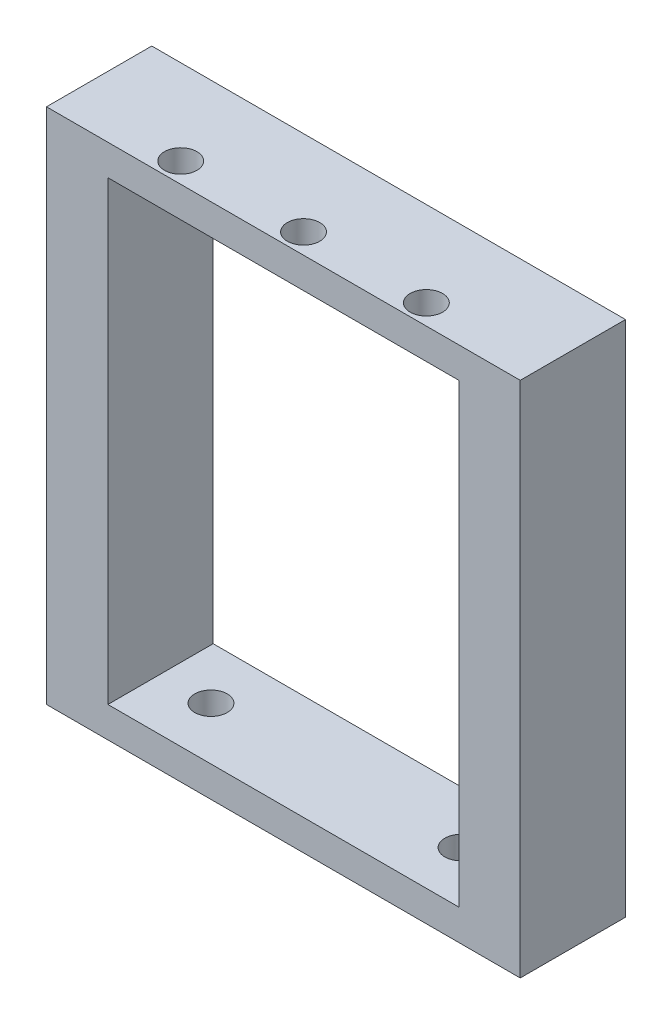
SolidWorks part; units mm, degrees
ref_plane "Front Plane" through (0, 0, 0) normal (0, 0, 1) x (1, 0, 0)
ref_plane "Top Plane" through (0, 0, 0) normal (0, 1, 0) x (1, 0, 0)
ref_plane "Right Plane" through (0, 0, 0) normal (1, 0, 0) x (0, 0, -1)
sketch "Sketch1" plane through (0, 0, 0) normal (0, 0, 1) x (1, 0, 0)
  line L1 (0, 0) -> (54, 0)
  line L2 (0, 0) -> (0, 59)
  line L3 (0, 59) -> (54, 59)
  line L4 (54, 0) -> (54, 59)
  line L8 (0, 59) -> (54, 0) construction
  line L10 (7, 3.5) -> (47, 3.5)
  line L11 (7, 3.5) -> (7, 55.5)
  line L12 (7, 55.5) -> (47, 55.5)
  line L13 (47, 3.5) -> (47, 55.5)
  line L14 (7, 3.5) -> (47, 55.5) construction
  line L15 (7, 55.5) -> (47, 3.5) construction
  point P5 (27, 29.5)
  dimension "D2" = 59
  dimension "D1" = 7
  dimension "D3" = 3.5
  dimension "D4" = 40
extrude "Boss-Extrude1" add sketch "Sketch1" along normal blind 12
sketch "Sketch2" plane through (0, 59, 0) normal (0, 1, 0) x (1, 0, 0)
  line L0 (13, -9.7) -> (41, -9.7) construction
  line L1 (27, 0) -> (27, -12) construction
  line L2 (54, 0) -> (0, 0) construction
  line L3 (54, -12) -> (0, -12) construction
  circle A0 centre (13, -9.7) radius 1.85
  circle A1 centre (41, -9.7) radius 1.85
  circle A2 centre (27, -9.7) radius 1.85
  point P10 (27, -7.1593)
  point P11 (27, -6)
  dimension "D1" = 3.7
  dimension "D3" = 3.7
  dimension "D2" = 14
  dimension "D4" = 3.7
extrude "Cut-Extrude1" cut sketch "Sketch2" against normal blind 10
sketch "Sketch3" plane through (0, 0, 0) normal (0, -1, 0) x (1, 0, 0)
  line L0 (27, 0) -> (27, 12) construction
  line L1 (0, 0) -> (54, 0) construction
  line L2 (0, 12) -> (54, 12) construction
  line L3 (27, 6) -> (12.75, 6) construction
  circle A0 centre (12.75, 6) radius 1.85
  circle A1 centre (41.25, 6) radius 1.85
  dimension "D1" = 3.7
  dimension "D2" = 14.25
extrude "Cut-Extrude2" cut sketch "Sketch3" against normal blind 10
